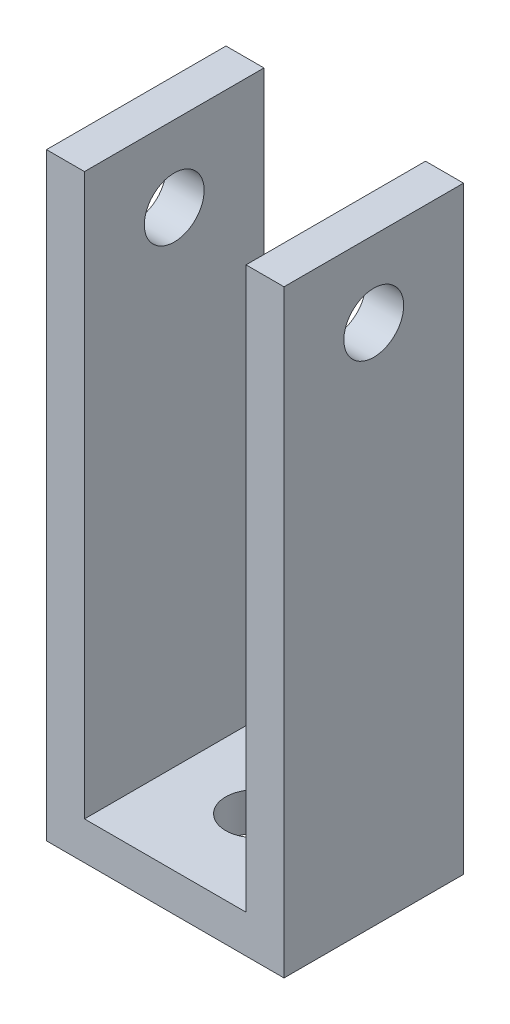
SolidWorks part; units mm, degrees
ref_plane "Alzado" through (0, 0, 0) normal (0, 0, 1) x (1, 0, 0)
ref_plane "Planta" through (0, 0, 0) normal (0, 1, 0) x (1, 0, 0)
ref_plane "Vista lateral" through (0, 0, 0) normal (1, 0, 0) x (0, 0, -1)
sketch "Croquis1" plane through (0, 0, 0) normal (0, 0, 1) x (1, 0, 0)
  line L0 (-13.5, 12.7) -> (-19.85, 12.7)
  line L1 (-19.85, 12.7) -> (-19.85, -87.35)
  line L2 (-19.85, -87.35) -> (19.85, -87.35)
  line L3 (0, -87.35) -> (0, -81)
  line L4 (13.5, -81) -> (-13.5, -81)
  line L5 (-13.5, -81) -> (-13.5, 12.7)
  line L6 (17.9406, 0) -> (-23.0543, 0) construction
  line L7 (0, 40.9698) -> (0, -77.9704) construction
  line L8 (19.85, 12.7) -> (19.85, -87.35)
  line L9 (13.5, 12.7) -> (19.85, 12.7)
  line L10 (13.5, -81) -> (13.5, 12.7)
  dimension "D1" = 6.35
  dimension "D2" = 6.35
  dimension "D3" = 13.5
  dimension "D4" = 12.7
  dimension "D5" = 81
extrude "Saliente-Extruir1" add sketch "Croquis1" along normal mid plane 30 contours L4 L5 L0 L1 L2 L3 | L10 L4 L3 L2 L8 L9
sketch "Croquis2" plane through (-19.85, 0, 0) normal (-1, 0, 0) x (0, 0, 1)
  circle A0 centre (0, 0) radius 5
  dimension "D1" = 10
extrude "Cortar-Extruir1" cut sketch "Croquis2" against normal blind 60
sketch "Croquis3" plane through (0, -87.35, 0) normal (0, -1, 0) x (1, 0, 0)
  circle A0 centre (0, 0) radius 4.9
  dimension "D1" = 9.8
extrude "Cortar-Extruir2" cut sketch "Croquis3" against normal blind 60
